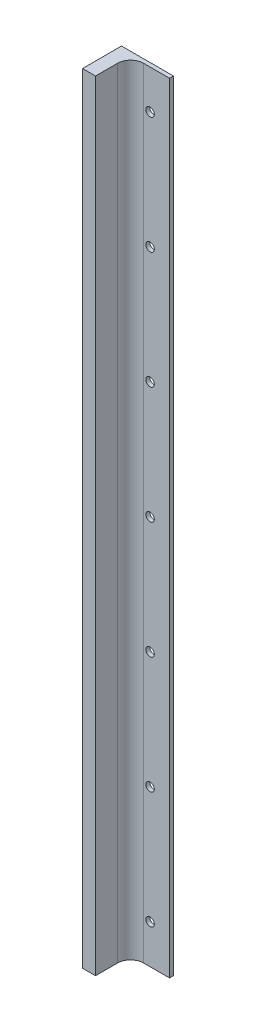
SolidWorks part; units mm, degrees
ref_plane "Front Plane" through (0, 0, 0) normal (0, 0, 1) x (1, 0, 0)
ref_plane "Top Plane" through (0, 0, 0) normal (0, 1, 0) x (1, 0, 0)
ref_plane "Right Plane" through (0, 0, 0) normal (1, 0, 0) x (0, 0, -1)
sketch "Sketch1" plane through (0, 0, 0) normal (0, 0, 1) x (1, 0, 0)
  line L1 (65, -300) -> (215, -300) construction
  line L3 (125, -300) -> (125, 300)
  line L4 (150, -300) -> (125, -300)
  line L5 (300, 300) -> (65, 300) construction
  line L6 (150, -300) -> (165, -300)
  line L7 (165, -300) -> (165, 300)
  line L8 (165, 300) -> (125, 300)
  circle A13 centre (150, 270) radius 3.25
  circle A14 centre (150, 180) radius 3.25
  circle A15 centre (150, 90) radius 3.25
  circle A16 centre (150, 0) radius 3.25
  circle A17 centre (150, -90) radius 3.25
  circle A18 centre (150, -180) radius 3.25
  circle A19 centre (150, -270) radius 3.25
extrude "Boss-Extrude1" add sketch "Sketch1" along normal blind 3
sketch "Sketch2" plane through (0, 0, 3) normal (0, 0, 1) x (1, 0, 0)
  line L0 (165, 300) -> (125, 300) construction
  line L1 (125, -300) -> (135, -300)
  line L2 (125, -300) -> (125, 300)
  line L3 (125, 300) -> (135, 300)
  line L4 (135, -300) -> (135, 300)
extrude "Boss-Extrude2" add sketch "Sketch2" along normal up to surface (27 mm away)
fillet "Fillet1" radius 10 1 edges at (135, 0, 3)
